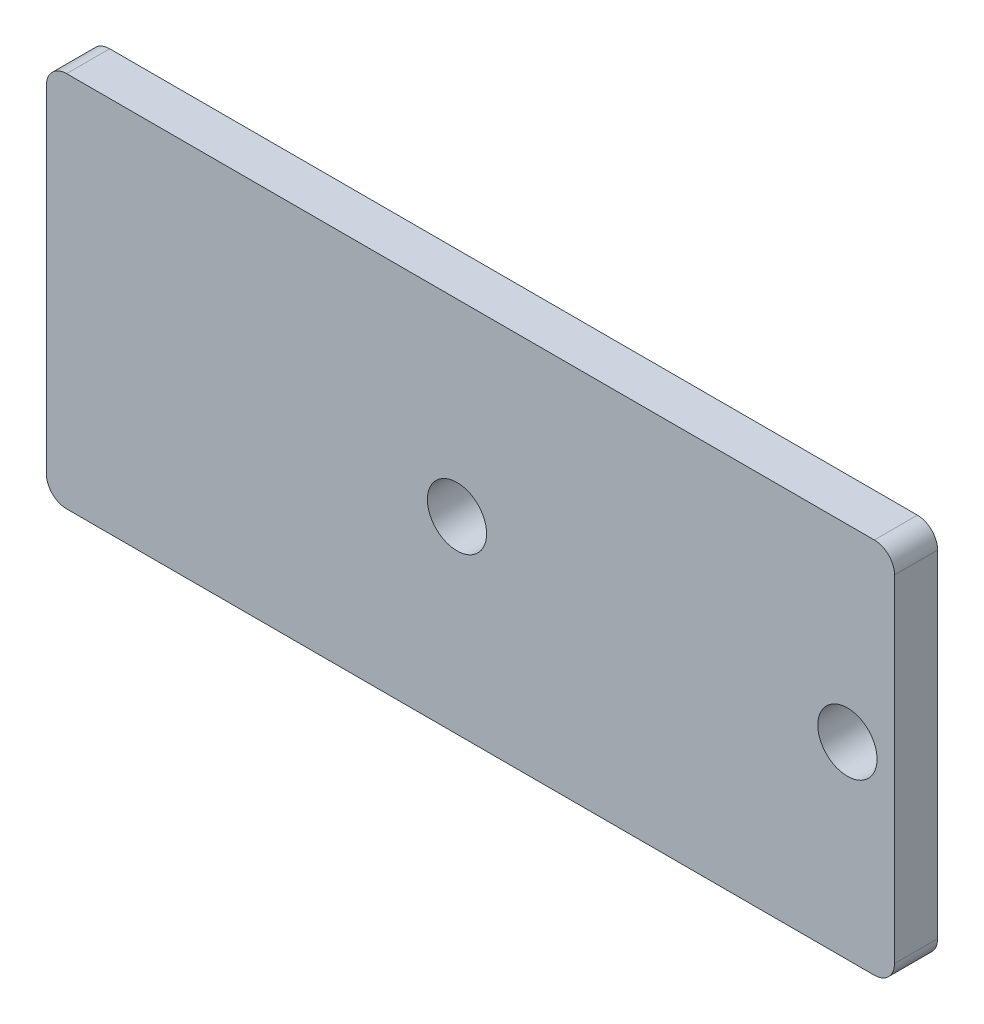
SolidWorks part; units mm, degrees
material "FR4_stuffedProtoboard"
ref_plane "Front Plane" through (0, 0, 0) normal (0, 0, 1) x (1, 0, 0)
ref_plane "Top Plane" through (0, 0, 0) normal (0, 1, 0) x (1, 0, 0)
ref_plane "Right Plane" through (0, 0, 0) normal (1, 0, 0) x (0, 0, -1)
sketch "Model" plane through (0, 0, 0) normal (0, 0, 1) x (1, 0, 0)
  line L0 (-15, -7) -> (15, -7)
  line L1 (15.75, -6.25) -> (15.75, 6.25)
  line L2 (15, 7) -> (-15, 7)
  line L3 (-15.75, 6.25) -> (-15.75, -6.25)
  arc A0 (15.75, 6.25) -> (15, 7) centre (15, 6.25) ccw
  arc A1 (15, -7) -> (15.75, -6.25) centre (15, -6.25) ccw
  arc A2 (-15.75, -6.25) -> (-15, -7) centre (-15, -6.25) ccw
  arc A3 (-15, 7) -> (-15.75, 6.25) centre (-15, 6.25) ccw
  circle A4 centre (-0.5, 0) radius 1.1
  circle A5 centre (14, 0) radius 1.1
  point P16 (0, 0)
  point P17 (0, 0)
  point P18 (0, 0)
  point P19 (0, 0)
  point P20 (0, 0)
  point P21 (0, 0)
  point P23 (0, 7)
  point P24 (15.75, 0)
  point P25 (0, 0)
  point P26 (0, 0)
  point P27 (15.7409, 6.3665)
  point P28 (15.7409, 6.3665)
  point P29 (-15.75, 6.25)
  point P30 (-15.75, -6.25)
  point P31 (-15.75, -6.25)
  point P32 (-15.75, -6.25)
  point P33 (-15.75, -6.25)
  point P34 (-15.75, 6.25)
  point P35 (-15, 6.25)
  point P36 (-15, 7)
  point P37 (-15.75, 6.25)
  point P38 (0, 0)
  point P39 (-15, 6.25)
  point P40 (-15.75, 6.25)
  dimension "D3" = 0.75
  dimension "D7" = 0.75
  dimension "D8" = 2.2
  dimension "D9" = 2.2
  dimension "D1" = 30
  dimension "D2" = 12.5
  dimension "D4" = 6.25
  dimension "D5" = 14.5
  dimension "D6" = 1.75
  dimension "D10" = 0.75
extrude "Boss-Extrude1" add sketch "Model" along normal mid plane 1.6
